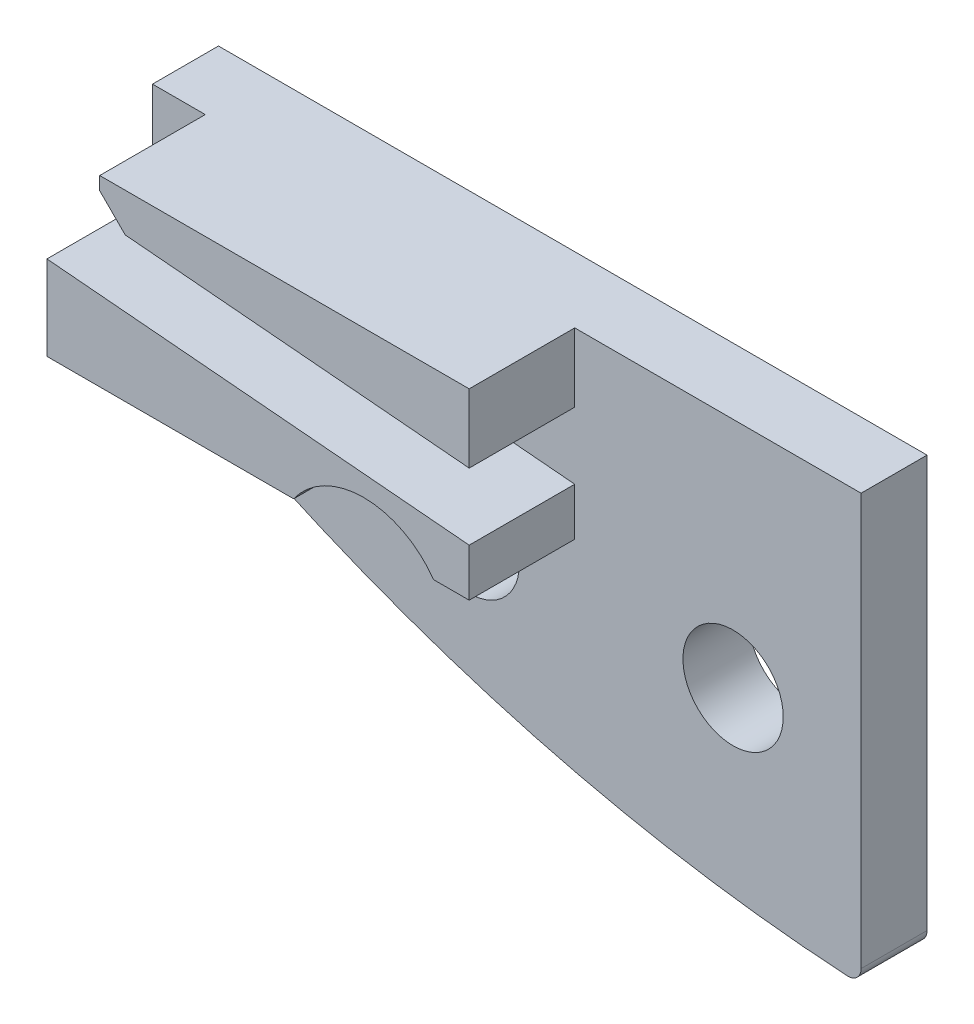
SolidWorks part; units mm, degrees
ref_plane "Front Plane" through (0, 0, 0) normal (0, 0, 1) x (1, 0, 0)
ref_plane "Top Plane" through (0, 0, 0) normal (0, 1, 0) x (1, 0, 0)
ref_plane "Right Plane" through (0, 0, 0) normal (1, 0, 0) x (0, 0, -1)
sketch "Sketch1" plane through (0, 0, 0) normal (0, 0, 1) x (1, 0, 0)
  line L0 (0, 0) -> (0, 76.2) construction
  line L1 (0, 20.5914) -> (-38.1, 20.5914)
  line L2 (-38.1, 20.5914) -> (-38.1, 10.2089)
  line L3 (-38.1, 16.1417) -> (0, 16.1417) construction
  line L4 (0, 20.5914) -> (0, 0)
  arc A0 (0, 0) -> (-38.1, 10.2089) centre (0, 76.2) cw
  circle A1 centre (-10.16, 9.398) radius 2.413
  circle A2 centre (-22.86, 9.398) radius 2.413
  dimension "D1" = 38.1
  dimension "D4" = 4.826
  dimension "D5" = 4.826
  dimension "D9" = 76.2
  dimension "D2" = 9.398
  dimension "D3" = 10.16
  dimension "D6" = 12.7
  dimension "D7" = 38.1
  dimension "D8" = 16.1417
extrude "Boss-Extrude1" add sketch "Sketch1" along normal blind 3.175
sketch "Sketch2" plane through (0, 0, 3.175) normal (0, 0, 1) x (1, 0, 0)
  line L0 (-22.86, 16.1417) -> (-38.1, 17.4693) construction
  line L2 (-38.1, 20.5914) -> (-38.1, 10.2089) construction
  line L3 (-38.1, 15.846) -> (-17.78, 14.0759)
  line L6 (-22.86, 16.1417) -> (-17.78, 15.6992) construction
  line L7 (-17.78, 20.5914) -> (-17.78, 1.616) construction
  line L9 (0, 20.5914) -> (-38.1, 20.5914) construction
  line L10 (-17.78, 17.2867) -> (-34.3322, 18.7286)
  line L11 (-34.3322, 18.7286) -> (-35.56, 19.9564)
  line L12 (-35.56, 19.9564) -> (-35.56, 20.5914)
  line L13 (-35.56, 20.5914) -> (-17.78, 20.5914)
  line L14 (-17.78, 20.5914) -> (-17.78, 17.2867)
  line L15 (-38.1, 15.846) -> (-38.1, 11.782)
  line L16 (-38.1, 11.782) -> (-17.78, 11.782)
  line L17 (-17.78, 11.782) -> (-17.78, 14.0759)
  point P0 (-22.86, 16.1417)
  dimension "D1" = 22.86
  dimension "D2" = 16.1417
  dimension "D3" = 15.24
  dimension "D4" = 17.4693
  dimension "D5" = 17.78
  dimension "D6" = 1.5875
  dimension "D7" = 17.78
  dimension "D8" = 45
  dimension "D9" = 0.635
  dimension "D10" = 4.064
extrude "Boss-Extrude2" add sketch "Sketch2" along normal blind 5.08
sketch "Sketch4" plane through (0, 0, 3.175) normal (0, 0, 1) x (1, 0, 0)
  line L0 (0, 0) -> (0, 36.7574) construction
  line L1 (0, 24.7848) -> (-4, 24.7848)
  line L2 (-4, 24.7848) -> (-4, 0)
  line L3 (-4, 0) -> (0, 0)
  line L4 (0, 24.7848) -> (0, 0)
  dimension "D1" = 4
  dimension "D2" = 0
extrude "Cut-Extrude2" cut sketch "Sketch4" against normal blind 5.08
fillet "Fillet1" radius 0.635 2 edges at (-38.1, 10.2089, 1.5875) (-4, 0.1051, 1.5875)
sketch "Sketch5" plane through (0, 0, 8.255) normal (0, 0, 1) x (1, 0, 0)
  circle A0 centre (-22.86, 9.398) radius 4.1275
  dimension "D1" = 8.255
extrude "Cut-Extrude3" cut sketch "Sketch5" against normal blind 5.08
ref_plane "Plane1" through (6.35, 0, 0) normal (1, 0, 0) x (0, 0, -1)
